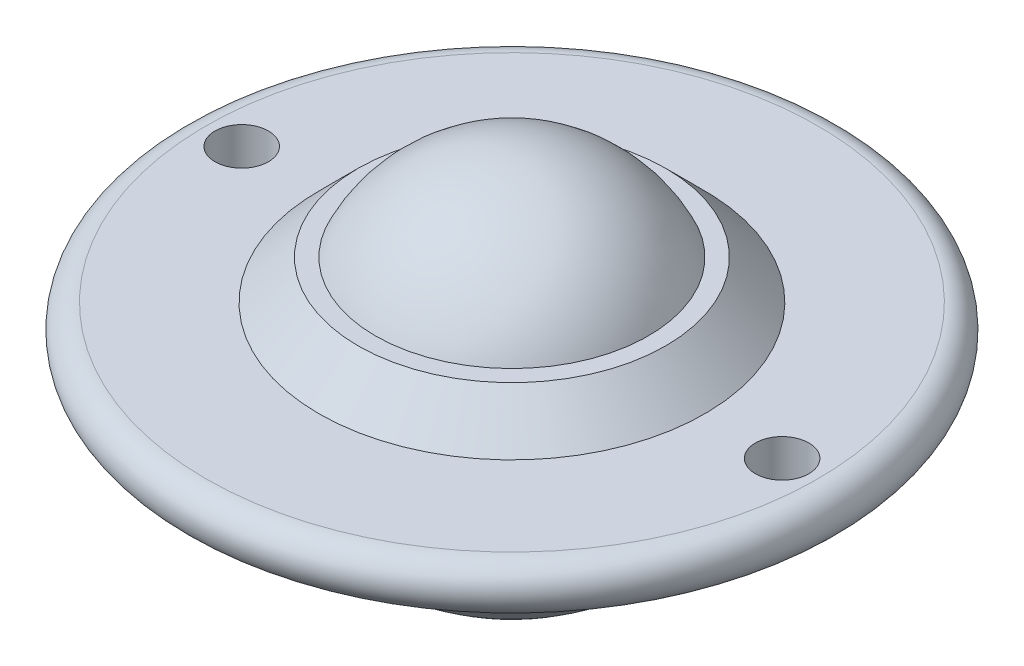
SolidWorks part; units mm, degrees
ref_plane "正面" through (0, 0, 0) normal (0, 0, 1) x (1, 0, 0)
ref_plane "平面" through (0, 0, 0) normal (0, 1, 0) x (1, 0, 0)
ref_plane "右側面" through (0, 0, 0) normal (1, 0, 0) x (0, 0, -1)
sketch "ｽｹｯﾁ1" plane through (0, 0, 0) normal (0, 0, 1) x (1, 0, 0)
  line L0 (0, 0) -> (50000, 0) construction
  line L1 (0, 0) -> (0, -50000) construction
  line L2 (-25.75, 2) -> (-16.25, 2)
  line L3 (-25.75, -2) -> (-17.3482, -2)
  line L4 (0, -17.2) -> (50000, -17.2) construction
  line L5 (0, 12.6) -> (0, -17.2)
  line L6 (-16.25, 2) -> (-12.95, 5.3)
  line L7 (-12.95, 5.3) -> (-11.4948, 5.3)
  line L8 (-16.25, 2) -> (-16.25, 5.3) construction
  line L9 (-16.25, 5.3) -> (-12.95, 5.3) construction
  arc A0 (-25.75, 2) -> (-25.75, -2) centre (-25.75, 0) ccw
  arc A1 (-17.3482, -2) -> (0, -17.2) centre (0, 0.3) ccw
  arc A2 (-11.4948, 5.3) -> (0, 12.6) centre (0, -0.1) cw
  point P24 (-27.75, 0)
  dimension "D1" = 17.5
  dimension "D7" = 12.7
  dimension "D2" = 4
  dimension "D3" = 15.2
  dimension "D4" = 55.5
  dimension "D5" = 32.5
  dimension "D6" = 7.3
  dimension "D8" = 14.6
revolve "回転1" add sketch "ｽｹｯﾁ1" angle 360 about L1
sketch "ｽｹｯﾁ2" plane through (0, -2, 0) normal (0, -1, 0) x (1, 0, 0)
  line L0 (0, 0) -> (50000, 0) construction
  line L1 (0, 0) -> (0, -50000) construction
  circle A0 centre (-22.75, 0) radius 2.25
  circle A1 centre (22.75, 0) radius 2.25
  dimension "D1" = 4.5
  dimension "D2" = 45.5
extrude "ｶｯﾄ - 押し出し1" cut sketch "ｽｹｯﾁ2" against normal through all
